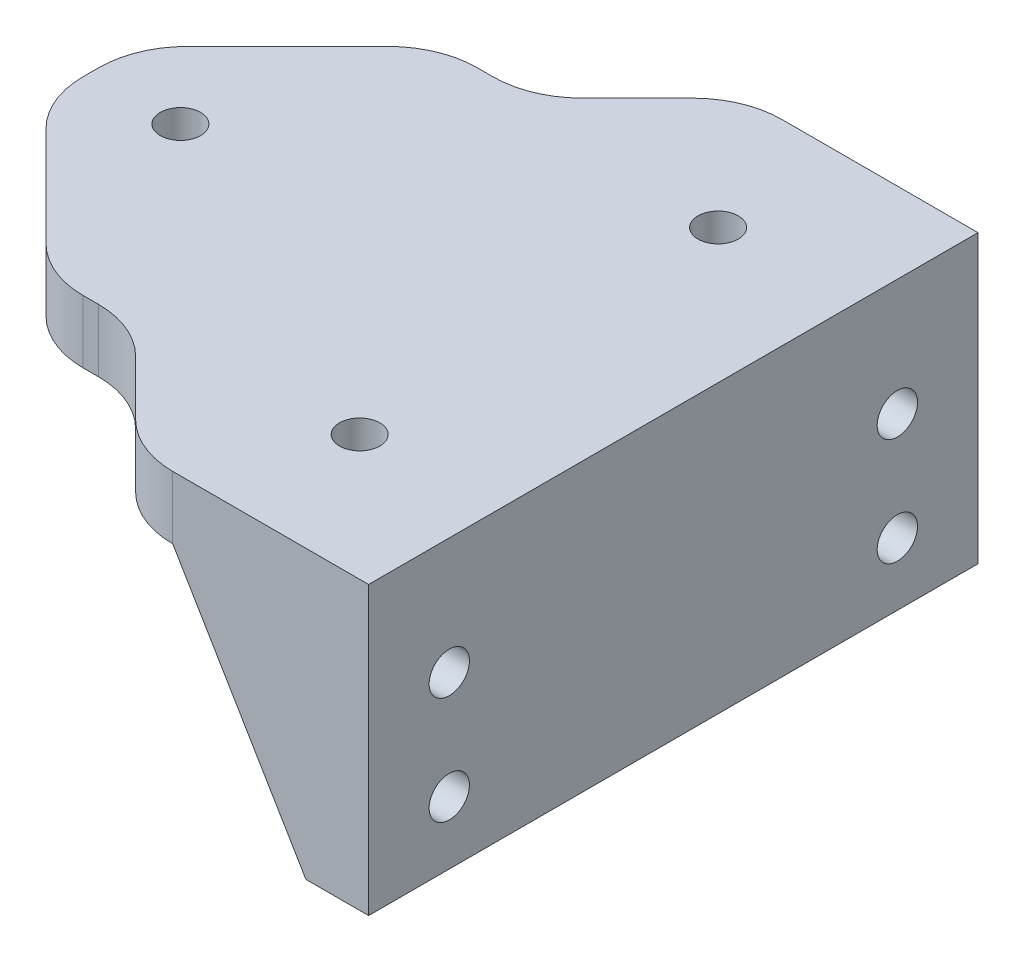
SolidWorks part; units mm, degrees
material "ABS"
ref_plane "Front Plane" through (0, 0, 0) normal (0, 0, 1) x (1, 0, 0)
ref_plane "Top Plane" through (0, 0, 0) normal (0, 1, 0) x (1, 0, 0)
ref_plane "Right Plane" through (0, 0, 0) normal (1, 0, 0) x (0, 0, -1)
sketch "Sketch1" plane through (0, 0, 0) normal (0, 1, 0) x (1, 0, 0)
  line L1 (0, 0) -> (60, 0)
  line L2 (0, 0) -> (0, 68)
  line L3 (0, 68) -> (60, 68)
  line L4 (60, 0) -> (60, 68)
  dimension "D1" = 68
  dimension "D2" = 60
extrude "Boss-Extrude1" add sketch "Sketch1" along normal blind 7
sketch "Sketch2" plane through (0, 0, 0) normal (0, 1, 0) x (1, 0, 0)
  line L0 (0, 68) -> (0, 0) construction
  line L1 (0, 7) -> (60, 7)
  line L2 (0, 7) -> (0, 0)
  line L3 (0, 0) -> (60, 0)
  line L4 (60, 7) -> (60, 0)
  dimension "D1" = 7
extrude "Boss-Extrude2" [suppressed] add sketch "Sketch2" against normal blind 20
hole_wizard "M4 Clearance Slot1" [suppressed] positions "Sketch3" profile "Sketch4" size "M4" standard "ANSI Metric"
sketch "Sketch3" plane through (0, 7, 0) normal (0, 1, 0) x (1, 0, 0)
  line L0 (32.05, 70) -> (32.05, 7) construction
  line L1 (64.1, 70) -> (0, 70) construction
  line L4 (16.235, 62.5) -> (47.865, 62.5) construction
  line L5 (47.865, 62.5) -> (47.865, 14.5) construction
  line L6 (47.865, 14.5) -> (16.235, 14.5) construction
  line L7 (16.235, 14.5) -> (16.235, 62.5) construction
  line L18 (40.365, 62.5) -> (55.365, 62.5) construction
  point P2 (47.865, 62.5)
  point P4 (47.865, 14.5)
  point P24 (16.235, 38.5)
  point P26 (32.05, 62.5)
  dimension "D1" = 31.63
  dimension "D2" = 48
  dimension "D3" = 15
  dimension "D4" = 31.5
sketch "Sketch4" plane through (47.865, 7, -62.5) normal (1, 0, 0) x (0, 0, 1)
  line L0 (0, 0) -> (0, 7)
  line L1 (0, 7) -> (2.25, 7)
  line L2 (2.25, 7) -> (2.25, 0)
  line L5 (2.25, 0) -> (0, 0)
  line L11 (0, -6.35) -> (0, 107.95) construction
  dimension "Thru Hole Dia." = 4.5
  dimension "Thru Hole Depth" = 7
hole_wizard "M2 Clearance Hole1" [suppressed] positions "Sketch8" profile "Sketch9" hole size "M2" standard "ANSI Metric"
sketch "Sketch8" plane through (0, 0, 0) normal (-1, 0, 0) x (0, 0, 1)
  line L4 (-29.5, 3.5) -> (-47.5, 3.5) construction
  line L7 (-70, 7) -> (-70, 0) construction
  point P0 (-47.5, 3.5)
  point P2 (-29.5, 3.5)
  point P23 (-70, 3.5)
  point P25 (-38.5, 3.5)
  dimension "D1" = 18
  dimension "D2" = 31.5
sketch "Sketch9" plane through (0, 3.5, -47.5) normal (0, 1, 0) x (0, 0, 1)
  line L0 (0, 0) -> (0, 35.721)
  line L1 (0, 35.721) -> (1.2, 35)
  line L2 (1.2, 35) -> (1.2, 0)
  line L5 (1.2, 0) -> (0, 0)
  line L10 (0, 35.721) -> (-1.2, 35) construction
  line L11 (0, -6.35) -> (0, 107.95) construction
  dimension "Hole Dia." = 2.4
  dimension "Hole Depth" = 35
  dimension "Drill Angle" = 118
sketch "Sketch11" plane through (0, 7, 0) normal (0, 1, 0) x (1, 0, 0)
  line L0 (0, 56) -> (28, 56)
  line L1 (0, 68) -> (0, 0) construction
  line L2 (28, 56) -> (40, 68)
  line L3 (60, 68) -> (0, 68) construction
  line L4 (0, 56) -> (0, 68)
  line L5 (0, 68) -> (40, 68)
  dimension "D1" = 135
  dimension "D2" = 12
  dimension "D3" = 40
extrude "Cut-Extrude2" [suppressed] cut sketch "Sketch11" against normal through all
sketch "Sketch12" [suppressed] plane through (0, 7, 0) normal (0, 1, 0) x (1, 0, 0)
  line L0 (18.475, 58) -> (18.475, 21.5)
  line L1 (0, 58) -> (28, 58) construction
  line L2 (18.475, 21.5) -> (0, 21.5)
  line L3 (0, 58) -> (0, 0) construction
  line L4 (0, 20.5) -> (19.475, 20.5)
  line L5 (19.475, 20.5) -> (19.475, 58)
  line L6 (19.475, 58) -> (18.475, 58)
  line L7 (0, 20.5) -> (0, 21.5)
  line L8 (0, 58) -> (0, 0) construction
  dimension "D3" = 18.475
  dimension "D1" = 1
  dimension "D2" = 1
  dimension "D4" = 36.5
extrude "Cut-Extrude3" [suppressed] cut sketch "Sketch12" against normal through all
sketch "Sketch13" [suppressed] plane through (0, 7, 0) normal (0, 1, 0) x (1, 0, 0)
  line L0 (19.475, 58) -> (28, 58) construction
  line L1 (24.475, 51.25) -> (27.975, 51.25)
  line L2 (24.475, 51.25) -> (24.475, 25)
  line L3 (24.475, 25) -> (27.975, 25)
  line L4 (27.975, 51.25) -> (27.975, 25)
  line L5 (19.475, 20.5) -> (19.475, 58) construction
  point P6 (26.225, 51.25)
  dimension "D1" = 3.5
  dimension "D2" = 26.25
  dimension "D3" = 5
  dimension "D4" = 6.75
extrude "Cut-Extrude4" [suppressed] cut sketch "Sketch13" against normal through all
sketch "Sketch14" [suppressed] plane through (64.1, 0, 0) normal (1, 0, 0) x (0, 0, -1)
  line L0 (70, 0) -> (7, -20)
  line L1 (7, -20) -> (7, 0)
  line L2 (7, 0) -> (70, 0)
extrude "Boss-Extrude3" [suppressed] add sketch "Sketch14" against normal blind 3
sketch "Sketch15" [suppressed] plane through (0, 0, 0) normal (-1, 0, 0) x (0, 0, 1)
  line L0 (-19.5, 0) -> (-7, -20)
  line L1 (-7, -20) -> (-7, 0)
  line L2 (-7, 0) -> (-19.5, 0)
extrude "Boss-Extrude4" [suppressed] add sketch "Sketch15" against normal blind 3
ref_plane "Plane1" [suppressed] through (28, 0, 0) normal (1, 0, 0) x (0, 0, -1)
sketch "Sketch16" [suppressed] plane through (28, 0, 0) normal (1, 0, 0) x (0, 0, -1)
  line L0 (58, 0) -> (7, 0)
  line L1 (7, 0) -> (7, -20)
  line L2 (7, -20) -> (58, 0)
extrude "Boss-Extrude5" [suppressed] add sketch "Sketch16" against normal blind 3
hole_wizard "M4 Clearance Hole1" [suppressed] positions "Sketch17" profile "Sketch18" hole size "M4" standard "ANSI Metric"
sketch "Sketch17" [suppressed] plane through (0, 0, -7) normal (0, 0, -1) x (-1, 0, 0)
  line L0 (-61.1, -11.5) -> (-3, -11.5) construction
  line L1 (-61.1, 0) -> (-61.1, -20) construction
  line L2 (-3, -20) -> (-3, 0) construction
  line L4 (-61.1, -20) -> (-28, -20) construction
  line L5 (-25, 0) -> (-25, -20) construction
  point P0 (-51.1, -11.5)
  point P2 (-36.1, -11.5)
  point P4 (-17, -11.5)
  point P6 (-7, -11.5)
  dimension "D1" = 8.5
  dimension "D2" = 10
  dimension "D3" = 15
  dimension "D4" = 8
  dimension "D5" = 10
sketch "Sketch18" plane through (51.1, -11.5, -7) normal (1, 0, 0) x (0, 1, 0)
  line L0 (0, 0) -> (0, 7)
  line L1 (0, 7) -> (2.25, 7)
  line L2 (2.25, 7) -> (2.25, 0)
  line L5 (2.25, 0) -> (0, 0)
  line L11 (0, -6.35) -> (0, 107.95) construction
  dimension "Thru Hole Dia." = 4.5
  dimension "Thru Hole Depth" = 7
fillet "Fillet1" [suppressed] radius 10
fillet "Fillet2" [suppressed] radius 2
hole_wizard "M4 Clearance Hole2" [suppressed] positions "Sketch20" profile "Sketch21" hole size "M4" standard "ANSI Metric"
sketch "Sketch20" plane through (0, 0, 0) normal (0, -1, 0) x (-1, 0, 0)
  line L0 (-25, 36.5) -> (-25, 21.5) construction
  line L2 (-25, 29) -> (0, 29) construction
  line L3 (0, 58) -> (0, 0) construction
  line L6 (-60, 58) -> (0, 58) construction
  point P0 (-25, 36.5)
  point P2 (-25, 21.5)
  dimension "D1" = 15
  dimension "D2" = 25
  dimension "D3" = 29
sketch "Sketch21" plane through (25, 0, -36.5) normal (1, 0, 0) x (0, 0, -1)
  line L0 (0, 0) -> (0, 7)
  line L1 (0, 7) -> (2.25, 7)
  line L2 (2.25, 7) -> (2.25, 0)
  line L5 (2.25, 0) -> (0, 0)
  line L11 (0, -6.35) -> (0, 107.95) construction
  dimension "Thru Hole Dia." = 4.5
  dimension "Thru Hole Depth" = 7
sketch "Sketch22" [suppressed] plane through (0, 0, 0) normal (0, -1, 0) x (1, 0, 0)
  line L0 (19.475, -58) -> (36.975, -58)
  line L1 (36.975, -58) -> (36.975, -20.5)
  line L2 (36.975, -20.5) -> (19.475, -20.5)
  line L3 (19.475, -20.5) -> (19.475, -58)
  line L4 (27.975, -51.25) -> (24.475, -51.25)
  line L5 (24.475, -51.25) -> (24.475, -25)
  line L6 (24.475, -25) -> (27.975, -25)
  line L7 (27.975, -25) -> (27.975, -51.25)
  dimension "D1" = 17.5
extrude "Boss-Extrude7" [suppressed] add sketch "Sketch22" along normal blind 4
hole_wizard "M4 Clearance Hole3" [suppressed] positions "Sketch23" profile "Sketch24" hole size "M4" standard "ANSI Metric"
sketch "Sketch23" [suppressed] plane through (19.475, 0, 0) normal (-1, 0, 0) x (0, 0, 1)
  line L0 (-58, 1.5) -> (-20.5, 1.5) construction
  line L1 (-58, -4) -> (-58, 7) construction
  line L2 (-20.5, 0) -> (-20.5, 7) construction
  point P0 (-47.5, 1.5)
  point P2 (-29.5, 1.5)
  dimension "D1" = 10.5
  dimension "D2" = 18
sketch "Sketch24" plane through (19.475, 1.5, -47.5) normal (0, 1, 0) x (0, 0, 1)
  line L0 (0, 0) -> (0, 15.8819)
  line L1 (0, 15.8819) -> (2.25, 14.53)
  line L2 (2.25, 14.53) -> (2.25, 0)
  line L5 (2.25, 0) -> (0, 0)
  line L10 (0, 15.8819) -> (-2.25, 14.53) construction
  line L11 (0, -6.35) -> (0, 107.95) construction
  dimension "Hole Dia." = 4.5
  dimension "Hole Depth" = 14.53
  dimension "Drill Angle" = 118
pattern_linear "LPattern1" [suppressed] count 2 spacing 13
hole_wizard "M4 Clearance Hole4" positions "Sketch27" profile "Sketch28" hole size "M4" standard "ANSI Metric" end condition through all
sketch "Sketch27" plane through (0, 0, 0) normal (0, -1, 0) x (-1, 0, 0)
  line L0 (-30, 0) -> (-30, 68) construction
  line L2 (-60, 68) -> (0, 68) construction
  line L4 (-50, 14) -> (-50, 54) construction
  line L6 (-10, 34) -> (-50, 34) construction
  line L7 (0, 0) -> (-60, 0) construction
  line L8 (-60, 0) -> (-60, 68) construction
  line L9 (-10, 34) -> (0, 34) construction
  line L10 (0, 68) -> (0, 0) construction
  point P0 (-50, 54)
  point P2 (-50, 14)
  point P4 (-10, 34)
  point P21 (-30, 34)
  dimension "D1" = 40
  dimension "D2" = 40
sketch "Sketch28" plane through (50, 0, -54) normal (1, 0, 0) x (0, 0, -1)
  line L0 (0, 0) -> (0, 7)
  line L1 (0, 7) -> (2.25, 7)
  line L2 (2.25, 7) -> (2.25, 0)
  line L5 (2.25, 0) -> (0, 0)
  line L11 (0, -6.35) -> (0, 107.95) construction
  dimension "Thru Hole Dia." = 4.5
  dimension "Thru Hole Depth" = 7
sketch "Sketch29" plane through (0, 0, 0) normal (0, -1, 0) x (1, 0, 0)
  line L0 (39, 0) -> (27, -12)
  line L1 (0, 0) -> (60, 0) construction
  line L2 (27, -12) -> (17, -12)
  line L3 (17, -12) -> (0, -29)
  line L4 (0, -68) -> (0, 0) construction
  line L5 (0, -34) -> (60, -34) construction
  line L6 (60, 0) -> (60, -68) construction
  line L7 (0, -29) -> (0, 0)
  line L8 (0, 0) -> (39, 0)
  line L9 (0, -39) -> (0, -68)
  line L10 (17, -56) -> (0, -39)
  line L11 (27, -56) -> (17, -56)
  line L12 (0, -68) -> (39, -68)
  line L13 (39, -68) -> (27, -56)
  dimension "D1" = 10
  dimension "D2" = 45
  dimension "D3" = 10
  dimension "D4" = 12
extrude "Cut-Extrude5" cut sketch "Sketch29" against normal through all
fillet "Fillet3" radius 10 8 edges at (39, 3.5, -68) (27, 3.5, -56) (17, 3.5, -56) (0, 3.5, -39) (0, 3.5, -29) (17, 3.5, -12) (39, 3.5, 0) (27, 3.5, -12)
sketch "Sketch30" plane through (60, 0, 0) normal (1, 0, 0) x (0, 0, -1)
  line L1 (0, 0) -> (68, 0)
  line L2 (0, 0) -> (0, 7)
  line L3 (0, 7) -> (68, 7)
  line L4 (68, 0) -> (68, 7)
extrude "Boss-Extrude8" add sketch "Sketch30" along normal blind 5
sketch "Sketch31" plane through (0, 0, 0) normal (0, -1, 0) x (1, 0, 0)
  line L0 (65, -68) -> (43.1421, -68) construction
  line L1 (65, 0) -> (58, 0)
  line L2 (65, 0) -> (65, -68)
  line L3 (65, -68) -> (58, -68)
  line L4 (58, 0) -> (58, -68)
  dimension "D1" = 7
extrude "Boss-Extrude9" add sketch "Sketch31" along normal blind 25
hole_wizard "M4 Clearance Hole5" positions "Sketch34" profile "Sketch35" hole size "M4" standard "ANSI Metric" end condition through all
sketch "Sketch34" plane through (65, 0, 0) normal (1, 0, 0) x (0, 0, -1)
  line L0 (59, 7) -> (59, -6) construction
  line L4 (59, -6) -> (59, -18) construction
  line L6 (0, 0) -> (68, 0) construction
  line L7 (68, -25) -> (68, 7) construction
  line L9 (9, -6) -> (59, -6) construction
  line L11 (9, -6) -> (9, -18) construction
  line L12 (9, -18) -> (59, -18) construction
  line L14 (0, 7) -> (0, -25) construction
  point P0 (59, -6)
  point P13 (59, -18)
  point P28 (9, -6)
  point P30 (9, -18)
  dimension "D1" = 6
  dimension "D2" = 12
  dimension "D3" = 9
  dimension "D4" = 9
sketch "Sketch35" plane through (65, -6, -59) normal (0, 1, 0) x (0, 0, -1)
  line L0 (0, 0) -> (0, 65)
  line L1 (0, 65) -> (2.25, 65)
  line L2 (2.25, 65) -> (2.25, 0)
  line L5 (2.25, 0) -> (0, 0)
  line L11 (0, -6.35) -> (0, 107.95) construction
  dimension "Thru Hole Dia." = 4.5
  dimension "Thru Hole Depth" = 65
sketch "Sketch36" plane through (0, 0, 0) normal (0, 0, 1) x (1, 0, 0)
  line L0 (58, -25) -> (43.1421, 0)
  line L1 (43.1421, 0) -> (58, 0)
  line L2 (58, 0) -> (58, -25)
extrude "Boss-Extrude12" add sketch "Sketch36" against normal blind 3
sketch "Sketch37" plane through (0, 0, -68) normal (0, 0, -1) x (-1, 0, 0)
  line L0 (-43.1421, 0) -> (-58, -25)
  line L1 (-58, -25) -> (-58, 0)
  line L2 (-58, 0) -> (-43.1421, 0)
extrude "Boss-Extrude13" add sketch "Sketch37" against normal blind 3
